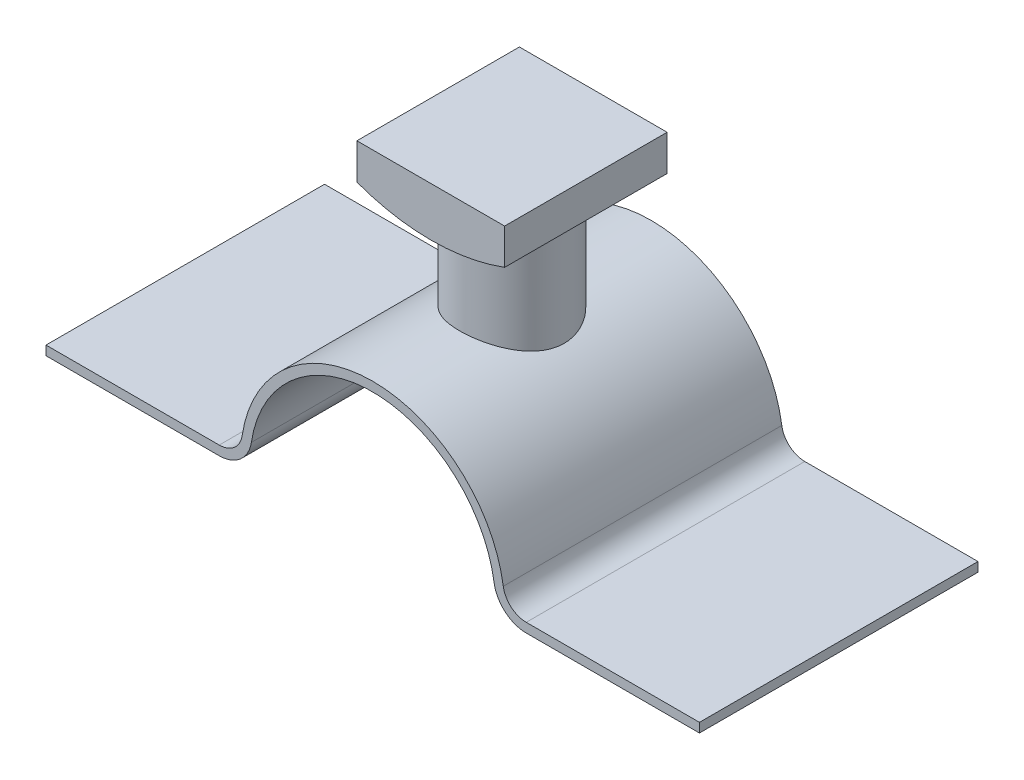
SolidWorks part; units mm, degrees
ref_plane "Front Plane" through (0, 0, 0) normal (0, 0, 1) x (1, 0, 0)
ref_plane "Top Plane" through (0, 0, 0) normal (0, 1, 0) x (1, 0, 0)
ref_plane "Right Plane" through (0, 0, 0) normal (1, 0, 0) x (0, 0, -1)
sketch "Sketch1" plane through (0, 0, 0) normal (0, 0, 1) x (1, 0, 0)
  line L0 (0, 0) -> (47.387, 0)
  line L1 (131.373, 0) -> (178.76, 0)
  line L2 (89.38, 70.151) -> (89.38, 47.4182) construction
  arc A0 (125.0944, 5.4006) -> (53.6656, 5.4006) centre (89.38, 0) ccw
  arc A1 (53.6656, 5.4006) -> (47.387, 0) centre (47.387, 6.35) cw
  arc A2 (131.373, 0) -> (125.0944, 5.4006) centre (131.373, 6.35) cw
  point P10 (125.5004, 0)
  dimension "D1" = 6.35
ref_plane "Plane1" through (0, 47.4182, 0) normal (0, 1, 0) x (-1, 0, 0)
sketch "Sketch2" plane through (0, 0, 0) normal (0, 0, 1) x (1, 0, 0)
  line L1 (69.175, 75.045) -> (109.585, 75.045)
  line L2 (69.175, 75.045) -> (69.175, 65.2569)
  line L4 (109.585, 75.045) -> (109.585, 65.2569)
  arc A0 (69.175, 65.2569) -> (109.585, 65.2569) centre (89.38, 119.895) ccw
  point P0 (89.38, 70.151)
sketch "Sketch3" plane through (0, 47.4182, 0) normal (0, 1, 0) x (-1, 0, 0)
  circle A0 centre (-89.38, 0) radius 14.2875
  dimension "D1" = 28.575
extrude "Extrude-Thin1" add sketch "Sketch1" along normal mid plane 76.2 thin
extrude "Extrude1" add sketch "Sketch2" along normal mid plane 44.45 separate body
extrude "Extrude2" add sketch "Sketch3" along normal up to body and the other way up to body
